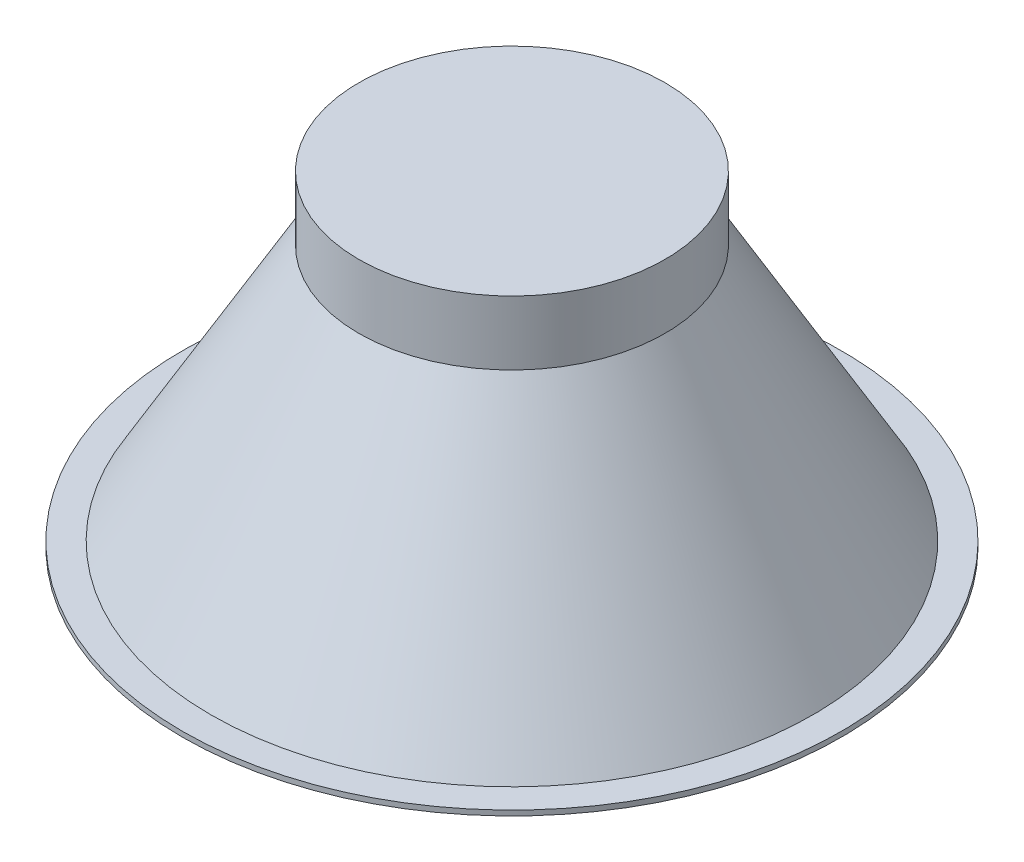
SolidWorks part; units mm, degrees
ref_plane "Front Plane" through (0, 0, 0) normal (0, 0, 1) x (1, 0, 0)
ref_plane "Top Plane" through (0, 0, 0) normal (0, 1, 0) x (1, 0, 0)
ref_plane "Right Plane" through (0, 0, 0) normal (1, 0, 0) x (0, 0, -1)
sketch "Sketch1" plane through (0, 0, 0) normal (0, 1, 0) x (1, 0, 0)
  circle A0 centre (0, 0) radius 128.5875
  dimension "D1" = 257.175
extrude "Boss-Extrude1" add sketch "Sketch1" along normal blind 2 contours A0
sketch "Sketch2" plane through (0, 2, 0) normal (0, 1, 0) x (1, 0, 0)
  circle A0 centre (0, 0) radius 117.475
  dimension "D1" = 234.95
extrude "Boss-Extrude2" add sketch "Sketch2" along normal blind 100 draft 30
sketch "Sketch6" plane through (0, 102, 0) normal (0, 1, 0) x (1, 0, 0)
  circle A0 centre (0, 0) radius 59.74
extrude "Boss-Extrude3" add sketch "Sketch6" along normal blind 25
